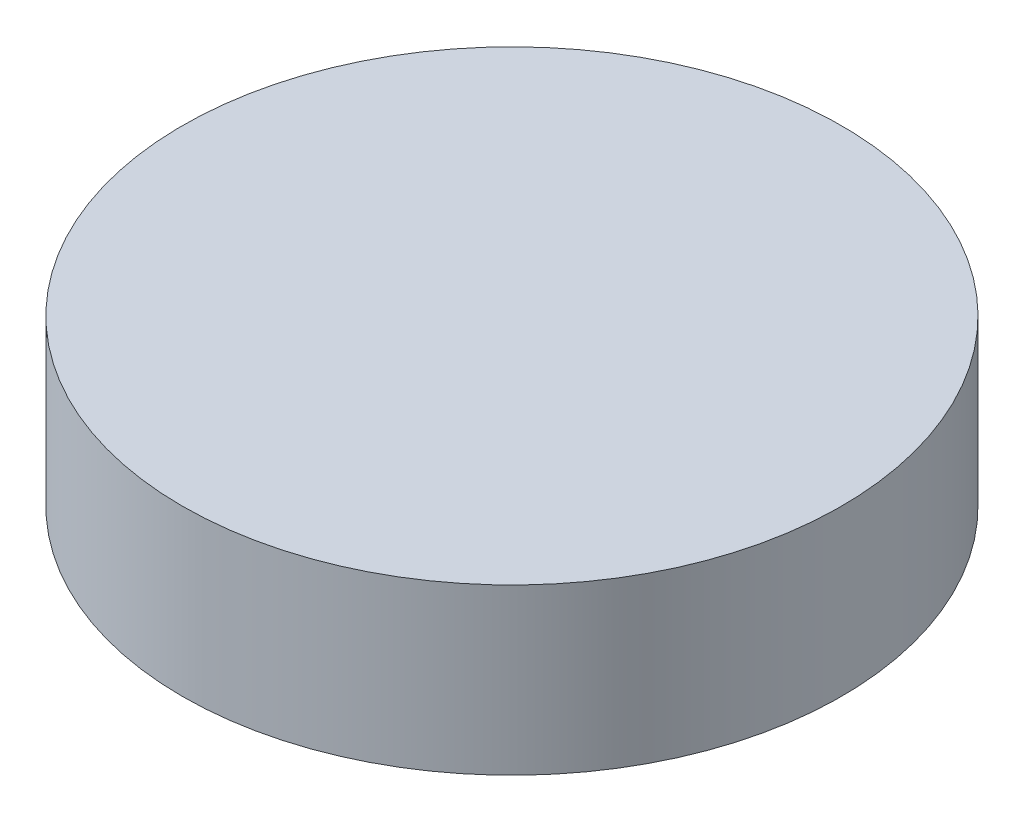
SolidWorks part; units mm, degrees
ref_plane "Front Plane" through (0, 0, 0) normal (0, 0, 1) x (1, 0, 0)
ref_plane "Top Plane" through (0, 0, 0) normal (0, 1, 0) x (1, 0, 0)
ref_plane "Right Plane" through (0, 0, 0) normal (1, 0, 0) x (0, 0, -1)
sketch "Sketch1" plane through (0, 0, 0) normal (0, 1, 0) x (1, 0, 0)
  circle A0 centre (0, 0) radius 30
  dimension "D1" = 60
extrude "Boss-Extrude1" add sketch "Sketch1" along normal blind 15
